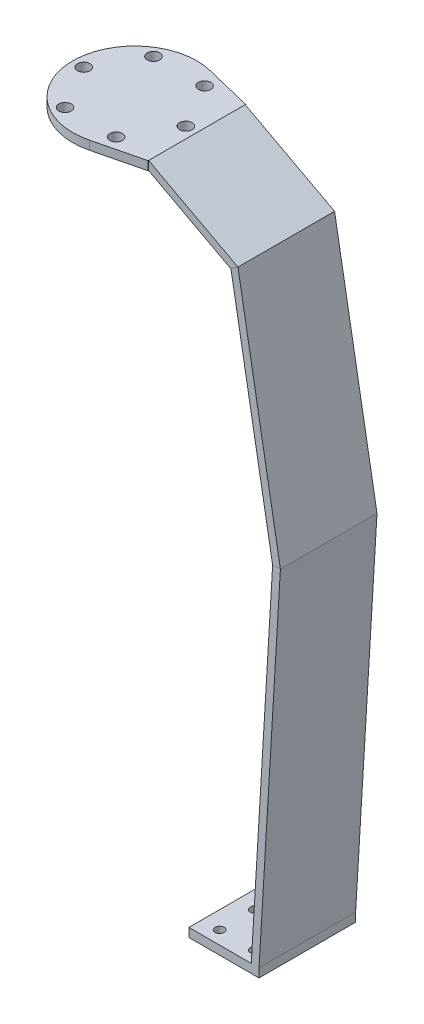
SolidWorks part; units mm, degrees
other "DetailItem2"
material "Copper"
ref_plane "Front Plane" through (0, 0, 0) normal (0, 0, 1) x (1, 0, 0)
ref_plane "Top Plane" through (0, 0, 0) normal (0, 1, 0) x (1, 0, 0)
ref_plane "Right Plane" through (0, 0, 0) normal (1, 0, 0) x (0, 0, -1)
ref_plane "40K Bottom Cold head Location" through (0, 236.49, 0) normal (0, 1, 0) x (1, 0, 0)
sketch "Sketch1" plane through (0, 0, 0) normal (0, 1, 0) x (1, 0, 0)
  line L0 (62.5, -17.5) -> (37.1, -17.5)
  line L5 (37.1, 17.5) -> (62.5, 17.5)
  line L6 (37.1, 17.5) -> (37.1, -17.5)
  line L8 (62.5, 17.5) -> (62.5, -17.5)
  circle A0 centre (43.45, 0) radius 1.63
  circle A6 centre (56.15, 0) radius 1.63
  circle A7 centre (43.45, 12.7) radius 1.63
  circle A8 centre (56.15, 12.7) radius 1.63
  circle A9 centre (43.45, -12.7) radius 1.63
  circle A10 centre (56.15, -12.7) radius 1.63
  point P6 (37.1, 0)
  dimension "D5" = 3.26
  dimension "D1" = 25.4
  dimension "D2" = 35
  dimension "D10" = 37.1
  dimension "D11" = 17.5
  dimension "D3" = 6.35
  dimension "D8" = 12.7
  dimension "D9" = 12.7
  dimension "D4" = 6.35
  dimension "D6" = 2
  dimension "D7" = 2
sketch "Sketch2" plane through (0, 236.49, 0) normal (0, 1, 0) x (1, 0, 0)
  line L0 (0, 22.5) -> (0, -22.5) construction
  line L1 (0, 0) -> (9.25, 16.0215) construction
  line L2 (0.25, 22.4986) -> (0.25, -22.4986)
  circle A1 centre (9.25, 16.0215) radius 2.25
  circle A5 centre (18.5, 0) radius 2.25
  circle A6 centre (9.25, -16.0215) radius 2.25
  circle A7 centre (-9.25, -16.0215) radius 2.25
  circle A8 centre (-18.5, 0) radius 2.25
  circle A9 centre (0, 0) radius 22.5
  circle A11 centre (-9.25, 16.0215) radius 2.25
  point P22 (0, 0)
  point P25 (0, 0)
  dimension "D3" = 4.5
  dimension "D8" = 45
  dimension "D2" = 18.5
  dimension "D4" = 30
  dimension "D10" = 0.25
  dimension "D6" = 18.5
  dimension "D7" = 18.5
  dimension "D5" = 6
ref_plane "Top_Connection_Plane" through (22.5, 0, 0) normal (1, 0, 0) x (0, 0, -1)
ref_plane "Bottom_Connection_Plane" through (58, 0, 0) normal (1, 0, 0) x (0, 0, -1)
extrude "Boss-Extrude1" add sketch "Sketch2" against normal blind 3.175
extrude "Boss-Extrude2" add sketch "Sketch1" along normal blind 3.175 separate body
sketch "Top_Connection_Sketch" plane through (22.5, 0, 0) normal (1, 0, 0) x (0, 0, -1)
  line L0 (69.5032, 236.49) -> (-69.5032, 236.49) construction
  line L1 (-17.5, 236.49) -> (17.5, 236.49)
  line L2 (-17.5, 236.49) -> (-17.5, 233.315)
  line L3 (-17.5, 233.315) -> (17.5, 233.315)
  line L4 (17.5, 236.49) -> (17.5, 233.315)
  line L5 (-22.5, 233.315) -> (22.5, 233.315) construction
  point P6 (0, 233.315)
  dimension "D1" = 35
ref_plane "Plane1" through (0, 236.49, 0) normal (0, 1, 0) x (1, 0, 0)
sketch "Sketch8" plane through (0, 236.49, 0) normal (0, 1, 0) x (1, 0, 0)
  line L0 (22.5, 17.6489) -> (5.3591, 21.8525)
  line L1 (22.5, -17.5) -> (22.5, 17.5) construction
  line L2 (22.5, -17.6489) -> (5.3591, -21.8525)
  line L3 (22.5, 17.6489) -> (22.5, -17.6489)
  line L4 (20.75, 0) -> (22.5, 0)
  line L6 (20.75, 0) -> (19.3415, -11.4959)
  line L7 (19.3415, -11.4959) -> (5.3591, -21.8525)
  line L8 (20.75, 0) -> (19.3415, 11.4959)
  line L9 (19.3415, 11.4959) -> (5.3591, 21.8525)
  circle A0 centre (0, 0) radius 22.5 construction
  circle A1 centre (18.5, 0) radius 2.25 construction
  dimension "D2" = 13.9825
extrude "Boss-Extrude6" add sketch "Sketch8" against normal up to surface (3.175 mm away) contours L6 L7 L2 L3 L4 | L9 L8 L4 L3 L0 up to face at (9.25, 233.315, -13.7715)
sketch3d "3DSketch4"
  line L0 (22.5, 236.49, 0) -> (54.8718, 219.216, 0)
  line L1 (22.5, 236.49, 17.5) -> (22.5, 236.49, -17.5) construction
  line L2 (62.5, 3.175, 0) -> (70.25, 132.1574, 0)
  line L4 (70.25, 132.1574, 0) -> (54.8718, 219.216, 0)
  line L5 (62.5, 3.175, -17.5) -> (62.5, 3.175, 17.5) construction
sweep "Sweep1" add profiles "Top_Connection_Sketch" path "3DSketch4"
equation "\"Distance_From_Cold_Center\"=37.1"
equation "\"D10@Sketch1\"=\"Distance_From_Cold_Center\""
equation "\"D11@Sketch1\"=\"D2@Sketch1\"/2"
equation "\"Inside_Cold_Rod_Dia\"=52"
equation "\"40K_Cold_Head_Dia\"=45"
equation "\"D8@Sketch2\"=\"40K_Cold_Head_Dia\""
